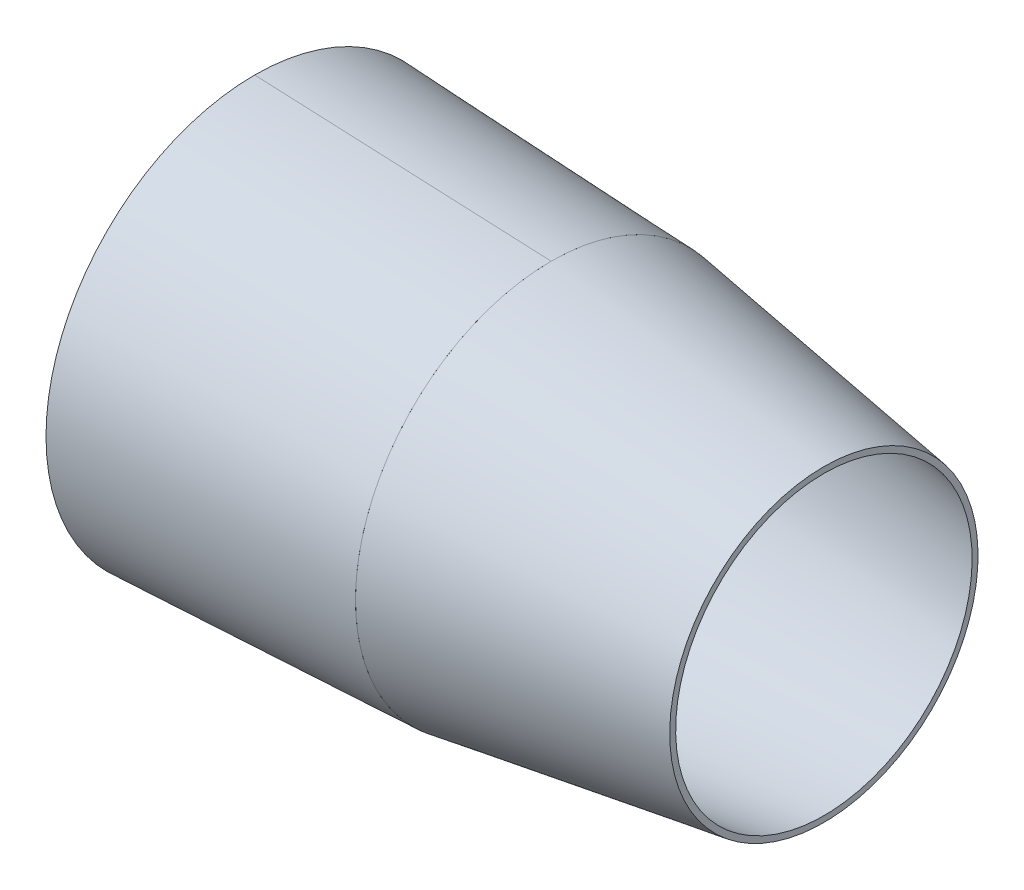
SolidWorks part; units mm, degrees
ref_plane "Front Plane" through (0, 0, 0) normal (0, 0, 1) x (1, 0, 0)
ref_plane "Top Plane" through (0, 0, 0) normal (0, 1, 0) x (1, 0, 0)
ref_plane "Right Plane" through (0, 0, 0) normal (1, 0, 0) x (0, 0, -1)
sketch "Sketch1" plane through (0, 0, 0) normal (0, 0, 1) x (1, 0, 0)
  line L0 (0, 0) -> (4000, 0) construction
  line L1 (700, 1720) -> (700, 1760)
  line L2 (700, 1760) -> (3200, 1650)
  line L3 (3200, 1650) -> (3200, 1610)
  line L4 (3200, 1610) -> (700, 1720)
revolve "Revolve1" add sketch "Sketch1" angle 180 about L0
sketch "Sketch2" plane through (0, 0, 0) normal (0, 0, 1) x (1, 0, 0)
  line L0 (0, 0) -> (4000, 0) construction
  line L1 (700, -1720) -> (700, -1760)
  line L2 (700, -1760) -> (3200, -1650)
  line L3 (3200, -1650) -> (3200, -1610)
  line L4 (3200, -1610) -> (700, -1720)
revolve "Revolve2" add sketch "Sketch2" angle 180 about L0
sketch "Sketch3" plane through (0, 0, 0) normal (0, 0, 1) x (1, 0, 0)
  line L0 (0, 0) -> (6000, 0) construction
  line L1 (3200, 1550) -> (3200, 1650)
  line L2 (3200, -1650) -> (3200, 1650) construction
  line L3 (3200, 1650) -> (5500, 1300)
  line L4 (5500, 1300) -> (5500, 1250)
  line L5 (5500, 1250) -> (3200, 1550)
revolve "Revolve3" add sketch "Sketch3" angle 360 about L0
